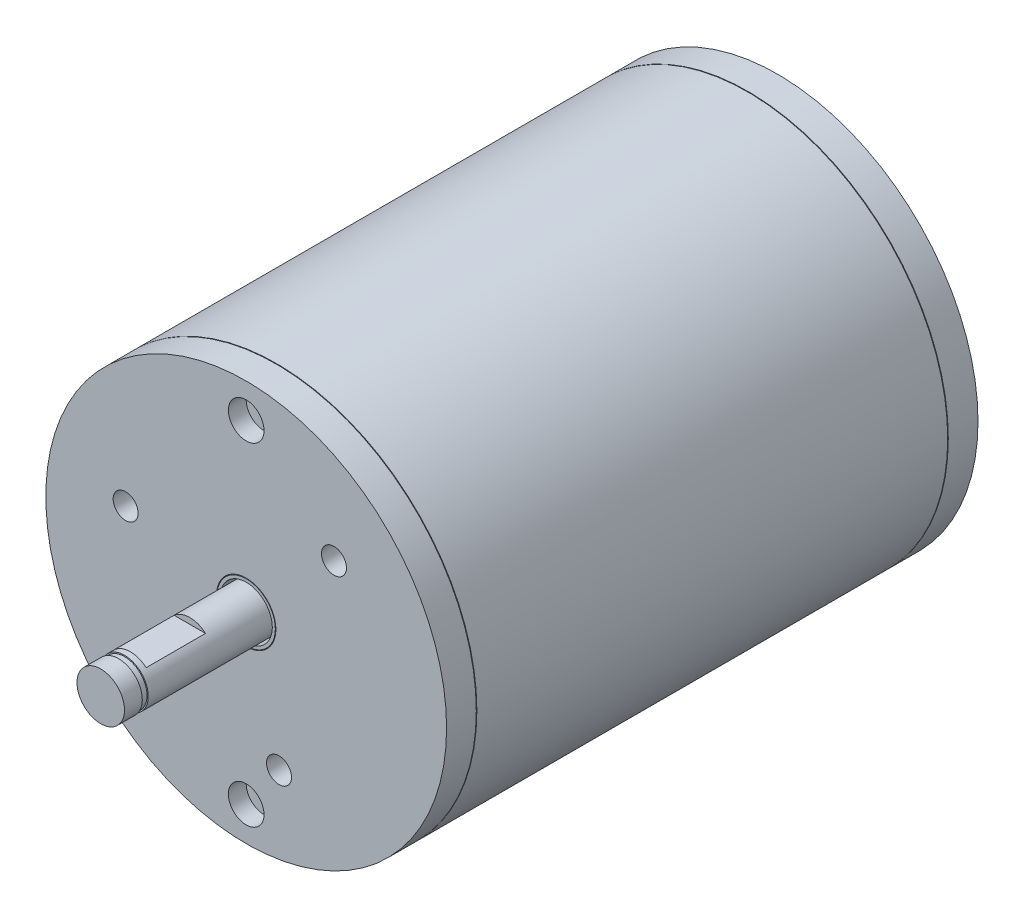
SolidWorks part; units mm, degrees
ref_plane "Front Plane" through (0, 0, 0) normal (0, 0, 1) x (1, 0, 0)
ref_plane "Top Plane" through (0, 0, 0) normal (0, 1, 0) x (1, 0, 0)
ref_plane "Right Plane" through (0, 0, 0) normal (1, 0, 0) x (0, 0, -1)
sketch "Sketch1" plane through (0, 0, 0) normal (0, 0, 1) x (1, 0, 0)
  circle A0 centre (0, 0) radius 33.75
  dimension "D1" = 67.5
extrude "Boss-Extrude1" add sketch "Sketch1" along normal blind 5
sketch "Sketch2" plane through (0, 0, 5) normal (0, 0, 1) x (1, 0, 0)
  circle A0 centre (0, 0) radius 33.6
  dimension "D1" = 67.2
extrude "Boss-Extrude2" add sketch "Sketch2" along normal blind 0.1
sketch "Sketch3" plane through (0, 0, 5.1) normal (0, 0, 1) x (1, 0, 0)
  circle A0 centre (0, 0) radius 33.75
  dimension "D1" = 67.5
extrude "Boss-Extrude3" add sketch "Sketch3" along normal blind 79.3
sketch "Sketch4" plane through (0, 0, 84.4) normal (0, 0, 1) x (1, 0, 0)
  circle A0 centre (0, 0) radius 33.6
  dimension "D1" = 67.2
extrude "Boss-Extrude4" add sketch "Sketch4" along normal blind 0.1
sketch "Sketch5" plane through (0, 0, 84.5) normal (0, 0, 1) x (1, 0, 0)
  circle A0 centre (0, 0) radius 33.75
  dimension "D1" = 67.5
extrude "Boss-Extrude5" add sketch "Sketch5" along normal blind 5
sketch "Sketch6" plane through (0, 0, 89.5) normal (0, 0, 1) x (1, 0, 0)
  circle A0 centre (0, 0) radius 21 construction
  circle A1 centre (14.3312, 15.3498) radius 2.1 construction
  circle A2 centre (6.1277, -20.0861) radius 2.1 construction
  circle A3 centre (-20.4589, 4.7363) radius 2.1 construction
  circle A4 centre (0, 0) radius 5
  dimension "D1" = 42
  dimension "D2" = 4.2
  dimension "D4" = 10
  dimension "D3" = 3
extrude "Cut-Extrude1" cut sketch "Sketch6" against normal blind 5
sketch "Sketch7" plane through (0, 0, 84.5) normal (0, 0, 1) x (1, 0, 0)
  circle A0 centre (0, 0) radius 4.9
  circle A1 centre (0, 0) radius 4.4
  dimension "D1" = 9.8
  dimension "D2" = 0.5
extrude "Boss-Extrude6" add sketch "Sketch7" along normal blind 5
sketch "Sketch8" plane through (0, 0, 84.5) normal (0, 0, 1) x (1, 0, 0)
  circle A0 centre (0, 0) radius 4
  dimension "D1" = 8
extrude "Boss-Extrude7" add sketch "Sketch8" along normal blind 24.5
sketch "Sketch9" plane through (0, 0, 0) normal (0, 0, -1) x (-1, 0, 0)
  circle A0 centre (0, 0) radius 15
  dimension "D1" = 30
extrude "Boss-Extrude8" add sketch "Sketch9" along normal blind 9.91
sketch "Sketch10" plane through (0, 0, 89.5) normal (0, 0, 1) x (1, 0, 0)
  circle A0 centre (0, 0) radius 21 construction
  circle A1 centre (14.7831, 14.9151) radius 1.75 construction
  circle A2 centre (5.5253, -20.2601) radius 1.75 construction
  circle A3 centre (-20.3084, 5.345) radius 1.75 construction
  dimension "D1" = 42
  dimension "D2" = 3.5
  dimension "D3" = 3
hole_wizard "M5 Tapped Hole1" positions "3DSketch1" profile "Sketch11" tap size "M5" standard "ISO"
sketch3d "3DSketch1"
  point P0 (-20.3084, 5.345, 89.5)
  point P3 (14.7831, 14.9151, 89.5)
  point P6 (5.5253, -20.2601, 89.5)
sketch "Sketch11" plane through (-20.3084, 5.345, 89.5) normal (1, 0, 0) x (0, -1, 0)
  line L0 (0, 0) -> (0, 6.2618)
  line L1 (0, 6.2618) -> (2.1, 5)
  line L2 (2.1, 5) -> (2.1, 0)
  line L5 (2.1, 0) -> (0, 0)
  line L10 (0, 6.2618) -> (-2.1, 5) construction
  line L11 (0, -6.35) -> (0, 107.95) construction
  dimension "Tap Drill Dia." = 4.2
  dimension "Tap Drill Depth" = 5
  dimension "Drill Angle" = 118
cosmetic thread "Hole Thread1" parameters "D1"=5, "D2"=5
cosmetic thread "Hole Thread2" parameters "D1"=5, "D2"=5
cosmetic thread "Hole Thread3" parameters "D1"=5, "D2"=5
ref_plane "Plane1" through (0, 4, 0) normal (0, 1, 0) x (1, 0, 0)
sketch "Sketch12" plane through (0, 4, 0) normal (0, 1, 0) x (1, 0, 0)
  line L1 (-4, -109) -> (4, -109)
  line L2 (-4, -109) -> (-4, -99)
  line L3 (-4, -99) -> (4, -99)
  line L4 (4, -109) -> (4, -99)
  dimension "D1" = 10
extrude "Cut-Extrude2" cut sketch "Sketch12" against normal blind 1 contours L4 L3 L2 L1
sketch "Sketch13" plane through (0, 0, 109) normal (0, 0, 1) x (1, 0, 0)
  circle A0 centre (0, 0) radius 4
extrude "Boss-Extrude9" add sketch "Sketch13" along normal blind 1
sketch "Sketch14" plane through (0, 0, 110) normal (0, 0, 1) x (1, 0, 0)
  circle A0 centre (0, 0) radius 3.8
  dimension "D1" = 7.6
extrude "Boss-Extrude10" add sketch "Sketch14" along normal blind 1
sketch "Sketch15" plane through (0, 0, 111) normal (0, 0, 1) x (1, 0, 0)
  circle A0 centre (0, 0) radius 4
  dimension "D1" = 8
extrude "Boss-Extrude11" add sketch "Sketch15" along normal blind 3
sketch "Sketch16" plane through (0, 0, 89.5) normal (0, 0, 1) x (1, 0, 0)
  circle A0 centre (0, 28) radius 3
  circle A1 centre (0, -28) radius 3
  dimension "D1" = 6
  dimension "D2" = 6
  dimension "D3" = 28
  dimension "D4" = 28
extrude "Cut-Extrude3" cut sketch "Sketch16" against normal blind 3
